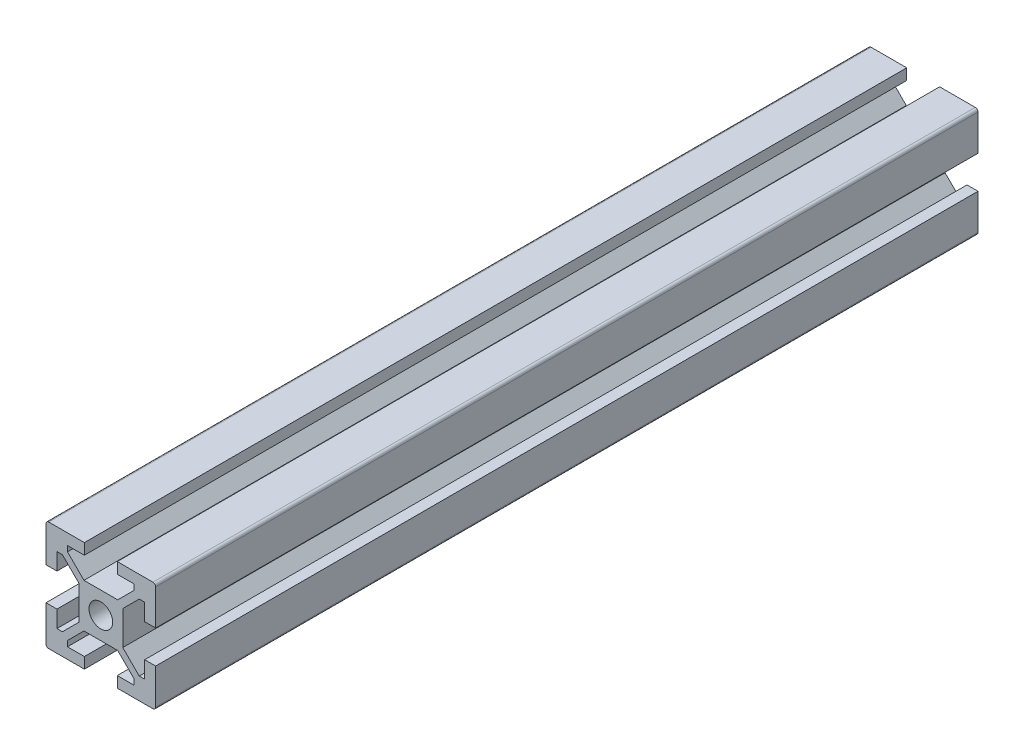
SolidWorks part; units mm, degrees
ref_plane "Front Plane" through (0, 0, 0) normal (0, 0, 1) x (1, 0, 0)
ref_plane "Top Plane" through (0, 0, 0) normal (0, 1, 0) x (1, 0, 0)
ref_plane "Right Plane" through (0, 0, 0) normal (1, 0, 0) x (0, 0, -1)
sketch "Sketch1" plane through (0, 0, 0) normal (0, 0, 1) x (1, 0, 0)
  line L0 (-3, 10) -> (-9.5, 10)
  line L1 (-10, 10) -> (10, 10) construction
  line L2 (-10, 10) -> (-10, -10) construction
  line L3 (-10, -10) -> (10, -10) construction
  line L4 (10, 10) -> (10, -10) construction
  line L5 (-10, 10) -> (10, -10) construction
  line L6 (-10, -10) -> (10, 10) construction
  line L7 (-8, 8) -> (8, 8) construction
  line L8 (-8, 8) -> (-8, -8) construction
  line L9 (-8, -8) -> (8, -8) construction
  line L10 (8, 8) -> (8, -8) construction
  line L11 (-8, 8) -> (8, -8) construction
  line L12 (-8, -8) -> (8, 8) construction
  line L13 (-4, 4) -> (4, 4) construction
  line L14 (-4, 4) -> (-4, -4) construction
  line L15 (-4, -4) -> (4, -4) construction
  line L16 (4, 4) -> (4, -4) construction
  line L17 (-4, 4) -> (4, -4) construction
  line L18 (-4, -4) -> (4, 4) construction
  line L19 (-3, 3) -> (3, 3) construction
  line L20 (-3, 3) -> (-3, -3) construction
  line L21 (-3, -3) -> (3, -3) construction
  line L22 (3, 3) -> (3, -3) construction
  line L23 (-3, 3) -> (3, -3) construction
  line L24 (-3, -3) -> (3, 3) construction
  line L25 (-10, 9.5) -> (-10, 3)
  line L26 (-10.4596, 9.5404) -> (9.5404, -10.4596) construction
  line L27 (-9.5404, -10.4596) -> (10.4596, 9.5404) construction
  line L28 (-9.5404, 10.4596) -> (10.4596, -9.5404) construction
  line L29 (-10.4596, -9.5404) -> (9.5404, 10.4596) construction
  line L30 (-10, 3) -> (-8, 3)
  line L31 (-8, 3) -> (-8, 6.0808)
  line L32 (-8, 6.0808) -> (-7, 6.0808)
  line L33 (-7, 6.0808) -> (-4, 3.0808)
  line L34 (-3, 10) -> (-3, 8)
  line L35 (-3, 8) -> (-6.0808, 8)
  line L36 (-6.0808, 8) -> (-6.0808, 7)
  line L37 (-6.0808, 7) -> (-3.0808, 4)
  line L38 (-3.0808, 4) -> (3.0808, 4)
  line L39 (3.0808, 4) -> (6.0808, 7)
  line L40 (6.0808, 7) -> (6.0808, 8)
  line L41 (6.0808, 8) -> (3, 8)
  line L42 (3, 8) -> (3, 10)
  line L43 (3, 10) -> (9.5, 10)
  line L44 (10, 9.5) -> (10, 3)
  line L45 (10, 3) -> (8, 3)
  line L46 (8, 3) -> (8, 6.0808)
  line L47 (8, 6.0808) -> (7, 6.0808)
  line L48 (7, 6.0808) -> (4, 3.0808)
  line L49 (4, 3.0808) -> (4, -3.0808)
  line L50 (4, -3.0808) -> (7, -6.0808)
  line L51 (7, -6.0808) -> (8, -6.0808)
  line L52 (8, -6.0808) -> (8, -3)
  line L53 (8, -3) -> (10, -3)
  line L54 (10, -3) -> (10, -9.5)
  line L55 (9.5, -10) -> (3, -10)
  line L56 (3, -10) -> (3, -8)
  line L57 (3, -8) -> (6.0808, -8)
  line L58 (6.0808, -8) -> (6.0808, -7)
  line L59 (6.0808, -7) -> (3.0808, -4)
  line L60 (3.0808, -4) -> (-3.0808, -4)
  line L61 (-3.0808, -4) -> (-6.0808, -7)
  line L62 (-6.0808, -7) -> (-6.0808, -8)
  line L63 (-6.0808, -8) -> (-3, -8)
  line L64 (-3, -8) -> (-3, -10)
  line L65 (-3, -10) -> (-9.5, -10)
  line L66 (-10, -9.5) -> (-10, -3)
  line L67 (-10, -3) -> (-8, -3)
  line L68 (-8, -3) -> (-8, -6.0808)
  line L69 (-8, -6.0808) -> (-7, -6.0808)
  line L70 (-7, -6.0808) -> (-4, -3.0808)
  line L71 (-4, -3.0808) -> (-4, 3.0808)
  circle A0 centre (0, 0) radius 2.15
  arc A1 (-9.5, -10) -> (-10, -9.5) centre (-9.5, -9.5) cw
  arc A2 (10, -9.5) -> (9.5, -10) centre (9.5, -9.5) cw
  arc A3 (9.5, 10) -> (10, 9.5) centre (9.5, 9.5) cw
  arc A4 (-9.5, 10) -> (-10, 9.5) centre (-9.5, 9.5) ccw
  point P0 (0, 0)
  point P6 (0, 0)
  dimension "D3" = 4.3
  dimension "D9" = 0.5
  dimension "D1" = 20
  dimension "D2" = 16
  dimension "D4" = 8
  dimension "D5" = 6
  dimension "D8" = 1
  dimension "D6" = 0.65
  dimension "D7" = 0.65
extrude "Boss-Extrude1" add sketch "Sketch1" along normal blind 150
